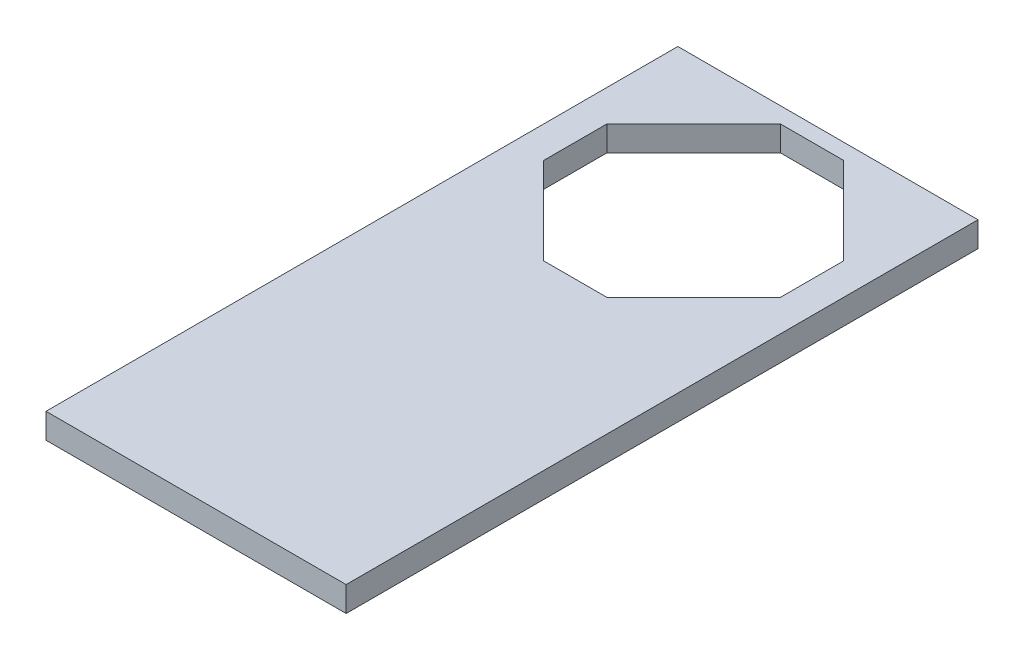
SolidWorks part; units mm, degrees
ref_plane "Front Plane" through (0, 0, 0) normal (0, 0, 1) x (1, 0, 0)
ref_plane "Top Plane" through (0, 0, 0) normal (0, 1, 0) x (1, 0, 0)
ref_plane "Right Plane" through (0, 0, 0) normal (1, 0, 0) x (0, 0, -1)
sketch "Sketch1" plane through (0, 0, 0) normal (0, 0, 1) x (1, 0, 0)
  line L1 (0, 0) -> (19, 0)
  line L2 (0, 0) -> (0, 1.5875)
  line L3 (0, 1.5875) -> (19, 1.5875)
  line L4 (19, 0) -> (19, 1.5875)
  dimension "D1" = 1.5875
  dimension "D2" = 19
extrude "Boss-Extrude1" add sketch "Sketch1" along normal blind 40 contours L3 L4 L1 L2
sketch "Sketch2" plane through (0, 1.5875, 0) normal (0, 1, 0) x (1, 0, 0)
  line L0 (9.5, 0) -> (9.5, -40) construction
  line L1 (2, -10.5) -> (7.5, -16)
  line L2 (2, -1) -> (17, -1) construction
  line L3 (2, -1) -> (2, -16) construction
  line L4 (2, -16) -> (17, -16) construction
  line L5 (17, -1) -> (17, -16) construction
  line L6 (2, -1) -> (17, -16) construction
  line L7 (0, 0) -> (19, 0) construction
  line L8 (0, -40) -> (19, -40) construction
  line L9 (2, -16) -> (17, -1) construction
  line L10 (7.5, -16) -> (11.5, -16)
  line L11 (11.5, -16) -> (17, -10.5)
  line L12 (17, -10.5) -> (17, -6.5)
  line L13 (17, -6.5) -> (11.5, -1)
  line L14 (11.5, -1) -> (7.5, -1)
  line L15 (7.5, -1) -> (2, -6.5)
  line L16 (2, -6.5) -> (2, -10.5)
  line L17 (2, -8.5) -> (17, -8.5) construction
  point P0 (9.5, -8.5)
  point P1 (9.5, -8.5)
  dimension "D1" = 15
  dimension "D2" = 15
  dimension "D3" = 2
  dimension "D5" = 2
  dimension "D10" = 8.5
extrude "Cut-Extrude1" cut sketch "Sketch2" against normal through all
